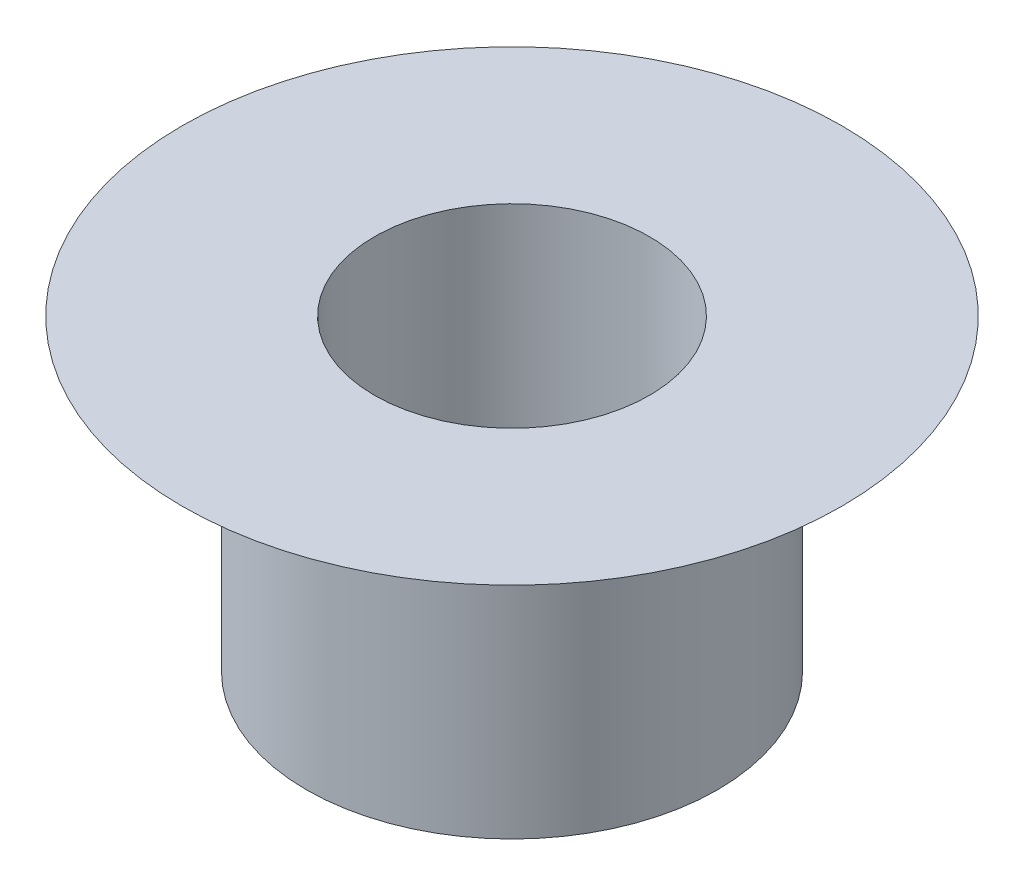
SolidWorks part; units mm, degrees
ref_plane "Front Plane" through (0, 0, 0) normal (0, 0, 1) x (1, 0, 0)
ref_plane "Top Plane" through (0, 0, 0) normal (0, 1, 0) x (1, 0, 0)
ref_plane "Right Plane" through (0, 0, 0) normal (1, 0, 0) x (0, 0, -1)
sketch "Sketch1" plane through (0, 0, 0) normal (0, 0, 1) x (1, 0, 0)
  line L0 (0, 75.5155) -> (0, -76.8265) construction
  line L1 (0, -49.5162) -> (-43, -49.5162)
  line L2 (-43, -49.5162) -> (-43, 4.4838)
  line L3 (-43, 4.4838) -> (-68.9994, 14.8775)
  line L4 (-68.9994, 14.8775) -> (0, 14.8775)
  line L5 (0, 14.8775) -> (0, -49.5162)
  dimension "D1" = 43
  dimension "D2" = 54
  dimension "D3" = 28
  dimension "D4" = 21.79
revolve "Revolve1" add sketch "Sketch1" angle 360 about L0
sketch "Sketch2" plane through (0, 14.8775, 0) normal (0, 1, 0) x (1, 0, 0)
  circle A0 centre (0, 0) radius 28.7798
extrude "Cut-Extrude1" cut sketch "Sketch2" against normal through all
